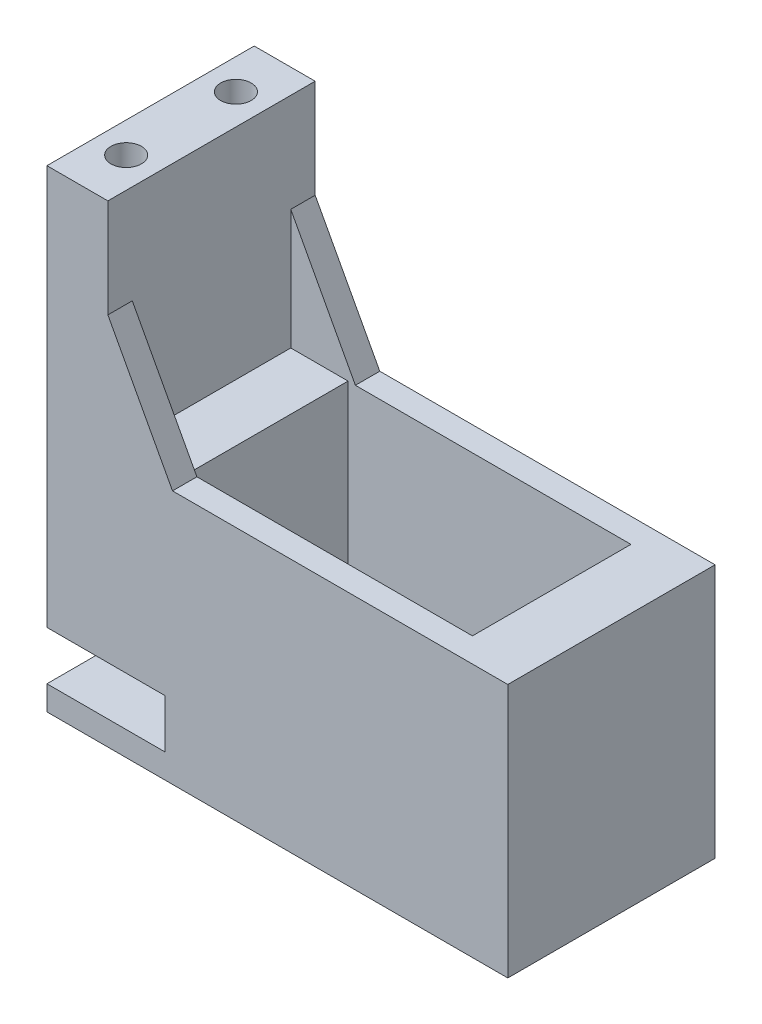
SolidWorks part; units mm, degrees
material "ABS"
ref_plane "Front Plane" through (0, 0, 0) normal (0, 0, 1) x (1, 0, 0)
ref_plane "Top Plane" through (0, 0, 0) normal (0, 1, 0) x (1, 0, 0)
ref_plane "Right Plane" through (0, 0, 0) normal (1, 0, 0) x (0, 0, -1)
sketch "Sketch1" plane through (0, 0, 0) normal (0, 0, 1) x (1, 0, 0)
  line L1 (-21.3, -15.7) -> (16.5, -15.7)
  line L2 (-21.3, -15.7) -> (-21.3, 5.15)
  line L3 (-21.3, 5.15) -> (16.5, 5.15)
  line L4 (16.5, -15.7) -> (16.5, 5.15)
extrude "Boss-Extrude1" add sketch "Sketch1" along normal mid plane 17
sketch "Sketch2" plane through (0, 0, 0) normal (0, 0, 1) x (1, 0, 0)
  line L1 (-21.3, 5.15) -> (-16.3, 5.15)
  line L2 (-21.3, 5.15) -> (-21.3, 23.1)
  line L3 (-21.3, 23.1) -> (-16.3, 23.1)
  line L4 (-16.3, 5.15) -> (-16.3, 23.1)
extrude "Boss-Extrude2" add sketch "Sketch2" along normal mid plane 17
ref_plane "Y+5_15" through (0, 5.15, 0) normal (0, 1, 0) x (1, 0, 0)
sketch "Sketch3" plane through (0, 5.15, 0) normal (0, 1, 0) x (1, 0, 0)
  line L1 (-11.6, -6.5) -> (11.6, -6.5)
  line L2 (-11.6, -6.5) -> (-11.6, 6.5)
  line L3 (-11.6, 6.5) -> (11.6, 6.5)
  line L4 (11.6, -6.5) -> (11.6, 6.5)
extrude "Cut-Extrude1" cut sketch "Sketch3" against normal blind 18.85
ref_plane "Y-13_70" through (0, -13.7, 0) normal (0, 1, 0) x (1, 0, 0)
sketch "Sketch4" plane through (0, -13.7, 0) normal (0, 1, 0) x (1, 0, 0)
  line L1 (11.6, -6.5) -> (13, -6.5)
  line L2 (11.6, -6.5) -> (11.6, 6.5)
  line L3 (11.6, 6.5) -> (13, 6.5)
  line L4 (13, -6.5) -> (13, 6.5)
extrude "Cut-Extrude3" cut sketch "Sketch4" along normal blind 5.8
sketch "Sketch5" plane through (0, 0, 0) normal (0, 0, 1) x (1, 0, 0)
  line L0 (9.35, -13.7) -> (-9.35, -13.7) construction
  line L1 (-21.3, -13.7) -> (-11.6, -13.7)
  line L2 (-21.3, -13.7) -> (-21.3, -9.7)
  line L3 (-21.3, -9.7) -> (-11.6, -9.7)
  line L4 (-11.6, -13.7) -> (-11.6, -9.7)
extrude "Cut-Extrude4" cut sketch "Sketch5" against normal through all and the other way through all
sketch "Sketch6" plane through (0, 0, 0) normal (0, 0, 1) x (1, 0, 0)
  line L0 (-16.3, 5.15) -> (-11, 5.15)
  line L1 (9.35, 5.15) -> (-9.35, 5.15) construction
  line L2 (-11, 5.15) -> (-16.3, 15)
  line L3 (-16.3, 5.15) -> (-16.3, 23.1) construction
  line L4 (-16.3, 15) -> (-16.3, 5.15)
extrude "Boss-Extrude3" add sketch "Sketch6" along normal mid plane 17
ref_plane "Y+15_00" through (0, 15, 0) normal (0, 1, 0) x (1, 0, 0)
sketch "Sketch7" plane through (0, 15, 0) normal (0, 1, 0) x (1, 0, 0)
  line L0 (-16.3, -8.5) -> (-16.3, 8.5) construction
  line L1 (-16.3, -6.5) -> (-11, -6.5)
  line L2 (-16.3, -6.5) -> (-16.3, 6.5)
  line L3 (-16.3, 6.5) -> (-11, 6.5)
  line L4 (-11, -6.5) -> (-11, 6.5)
extrude "Cut-Extrude5" cut sketch "Sketch7" against normal blind 9.85
ref_plane "Y-18_70" through (0, -18.7, 0) normal (0, 1, 0) x (1, 0, 0)
sketch "Sketch8" plane through (0, -18.7, 0) normal (0, 1, 0) x (1, 0, 0)
  circle A0 centre (5.5, 0) radius 3
extrude "Boss-Extrude4" add sketch "Sketch8" along normal blind 3
ref_plane "Y+23_10" through (0, 23.1, 0) normal (0, 1, 0) x (1, 0, 0)
sketch "Sketch9" plane through (0, 23.1, 0) normal (0, 1, 0) x (1, 0, 0)
  circle A0 centre (-18.8, -4.5) radius 1.25
extrude "Cut-Extrude6" cut sketch "Sketch9" against normal blind 4.3
sketch "Sketch10" plane through (0, 23.1, 0) normal (0, 1, 0) x (1, 0, 0)
  circle A0 centre (-18.8, 4.5) radius 1.25
extrude "Cut-Extrude7" cut sketch "Sketch10" against normal blind 4.3
ref_plane "X-24_10" through (-24.1, 0, 0) normal (1, 0, 0) x (0, 0, -1)
sketch "Sketch11" plane through (-24.1, 0, 0) normal (1, 0, 0) x (0, 0, -1)
  circle A0 centre (-4, -4) radius 1.5
  circle A1 centre (4, -4) radius 1.5
  circle A2 centre (-4, 4) radius 1.5
  circle A3 centre (4, 4) radius 1.5
extrude "Boss-Extrude5" add sketch "Sketch11" along normal blind 2.8
